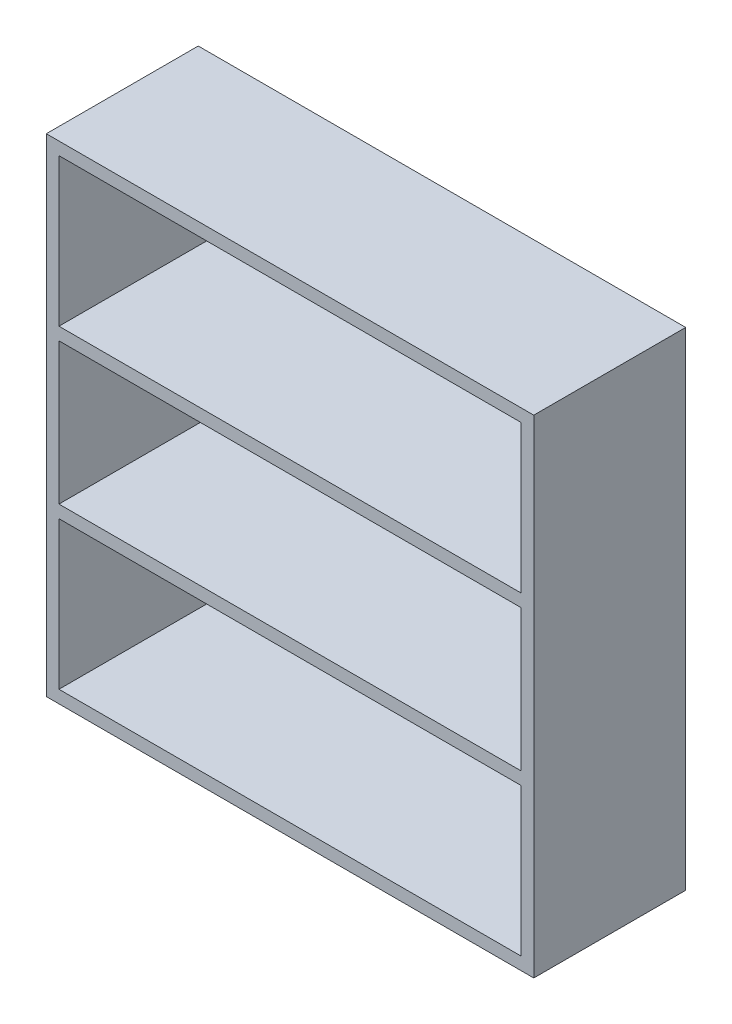
SolidWorks part; units mm, degrees
ref_plane "Front" through (0, 0, 0) normal (0, 0, 1) x (1, 0, 0)
ref_plane "Top" through (0, 0, 0) normal (0, 1, 0) x (1, 0, 0)
ref_plane "Right" through (0, 0, 0) normal (1, 0, 0) x (0, 0, -1)
sketch "Sketch1" plane through (0, 0, 0) normal (0, 1, 0) x (1, 0, 0)
  line L1 (-977.9, 304.8) -> (977.9, 304.8)
  line L2 (-977.9, 304.8) -> (-977.9, -304.8)
  line L3 (-977.9, -304.8) -> (977.9, -304.8)
  line L4 (977.9, 304.8) -> (977.9, -304.8)
  line L5 (-977.9, 304.8) -> (977.9, -304.8) construction
  line L6 (-977.9, -304.8) -> (977.9, 304.8) construction
  point P0 (0, 0)
  dimension "D1" = 1955.8
  dimension "D2" = 609.6
extrude "Boss-Extrude1" add sketch "Sketch1" along normal blind 1955.8
sketch "Sketch2" plane through (0, 0, 304.8) normal (0, 0, 1) x (1, 0, 0)
  line L0 (-927.1, 50.8) -> (927.1, 50.8)
  line L1 (927.1, 50.8) -> (927.1, 643.4667)
  line L2 (927.1, 1905) -> (-927.1, 1905)
  line L3 (-927.1, 1905) -> (-927.1, 1312.3333)
  line L4 (-977.9, 0) -> (977.9, 0)
  line L5 (977.9, 0) -> (977.9, 1955.8)
  line L6 (977.9, 1955.8) -> (-977.9, 1955.8)
  line L7 (-977.9, 1955.8) -> (-977.9, 0)
  line L8 (-977.9, 0) -> (977.9, 0) construction
  line L9 (977.9, 0) -> (977.9, 1955.8) construction
  line L10 (977.9, 1955.8) -> (-977.9, 1955.8) construction
  line L11 (-977.9, 1955.8) -> (-977.9, 0) construction
  line L12 (-927.1, 1286.9333) -> (927.1, 1286.9333) construction
  line L13 (-927.1, 668.8667) -> (927.1, 668.8667) construction
  line L14 (0, 1286.9333) -> (0, 1905) construction
  line L15 (0, 1286.9333) -> (0, 668.8667) construction
  line L16 (0, 668.8667) -> (0, 50.8) construction
  line L17 (-927.1, 1261.5333) -> (927.1, 1261.5333)
  line L18 (-927.1, 643.4667) -> (927.1, 643.4667)
  line L19 (-927.1, 1312.3333) -> (927.1, 1312.3333)
  line L20 (-927.1, 694.2667) -> (927.1, 694.2667)
  line L21 (-927.1, 1261.5333) -> (-927.1, 694.2667)
  line L22 (-927.1, 1905) -> (-927.1, 50.8) construction
  line L23 (-927.1, 643.4667) -> (-927.1, 50.8)
  line L24 (927.1, 694.2667) -> (927.1, 1261.5333)
  line L25 (927.1, 50.8) -> (927.1, 1905) construction
  line L26 (927.1, 1312.3333) -> (927.1, 1905)
  dimension "D1" = 0
  dimension "D2" = 50.8
  dimension "D3" = 25.4
  dimension "D4" = 25.4
extrude "Cut-Extrude1" cut sketch "Sketch2" against normal through all
